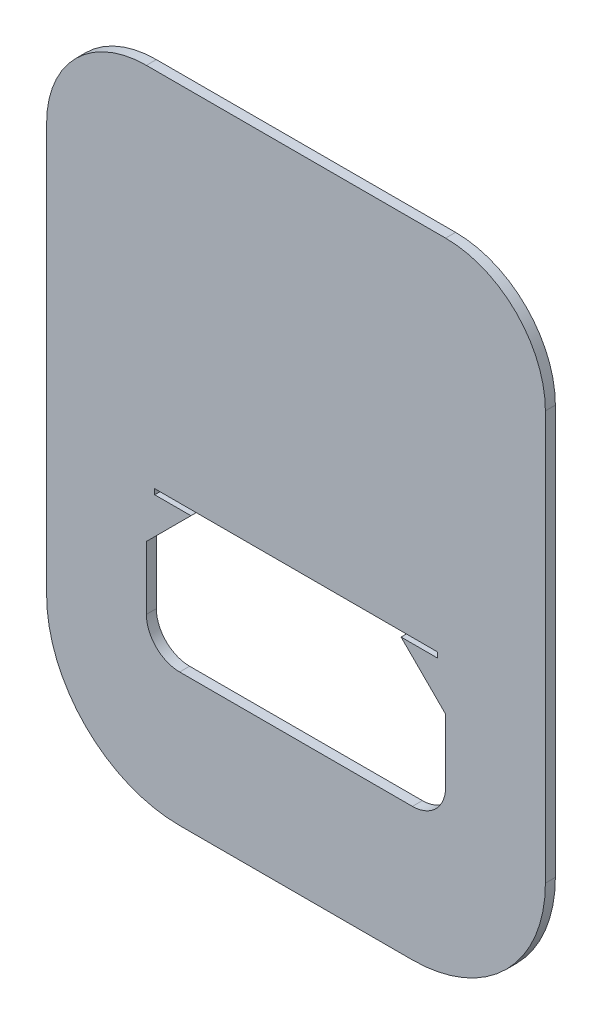
SolidWorks part; units mm, degrees
ref_plane "Front Plane" through (0, 0, 0) normal (0, 0, 1) x (1, 0, 0)
ref_plane "Top Plane" through (0, 0, 0) normal (0, 1, 0) x (1, 0, 0)
ref_plane "Right Plane" through (0, 0, 0) normal (1, 0, 0) x (0, 0, -1)
sketch "Sketch1" plane through (0, 0, 0) normal (0, 0, 1) x (1, 0, 0)
  line L0 (0, 96.5) -> (0, -96.5) construction
  line L1 (-75, 96.5) -> (75, 96.5) construction
  line L2 (-75, 96.5) -> (-75, -96.5) construction
  line L3 (-75, -96.5) -> (75, -96.5) construction
  line L4 (75, 96.5) -> (75, -96.5) construction
  line L5 (-45, 96.5) -> (45, 96.5)
  line L6 (-35, -96.5) -> (35, -96.5) construction
  line L7 (-75, 66.5) -> (75, 66.5) construction
  line L8 (-75, 66.5) -> (-75, -56.5)
  line L9 (-75, -56.5) -> (75, -56.5) construction
  line L10 (75, 66.5) -> (75, -56.5)
  line L11 (-0.5, -96.5) -> (0.5, -96.5) construction
  line L12 (-35, -96.5) -> (-0.5, -96.5)
  line L13 (0.5, -96.5) -> (35, -96.5)
  line L14 (-0.5, -96.5) -> (0.5, -96.5)
  arc A0 (-75, 66.5) -> (-45, 96.5) centre (-45, 66.5) cw
  arc A1 (45, 96.5) -> (75, 66.5) centre (45, 66.5) cw
  arc A2 (-75, -56.5) -> (-35, -96.5) centre (-35, -56.5) ccw
  arc A3 (35, -96.5) -> (75, -56.5) centre (35, -56.5) ccw
  point P10 (0, 96.5)
  point P19 (0, -96.5)
  point P23 (0, -96.5)
  dimension "D3" = 40
  dimension "D4" = 30
  dimension "D1" = 193
  dimension "D2" = 150
  dimension "D5" = 1
  dimension "D6" = 96.5
extrude "Boss-Extrude1" add sketch "Sketch1" along normal blind 3
sketch "Sketch2" plane through (0, 0, 3) normal (0, 0, 1) x (1, 0, 0)
  line L0 (0, -1.65) -> (0, 1.65) construction
  line L1 (-38, -56.5) -> (38, -56.5) construction
  line L2 (-45, -49.5) -> (-45, -19.5) construction
  line L3 (-38, -12.5) -> (38, -12.5) construction
  line L4 (45, -49.5) -> (45, -19.5) construction
  line L5 (-45, -56.5) -> (45, -12.5) construction
  line L6 (-45, -12.5) -> (45, -56.5) construction
  line L7 (-35, -96.5) -> (35, -96.5) construction
  line L9 (-45, -56.5) -> (45, -56.5)
  line L10 (-45, -56.5) -> (-45, -12.5)
  line L11 (-45, -12.5) -> (45, -12.5)
  line L12 (45, -56.5) -> (45, -12.5)
  line L13 (-45, -56.5) -> (45, -12.5) construction
  line L14 (-45, -12.5) -> (45, -56.5) construction
  arc A0 (38, -56.5) -> (45, -49.5) centre (38, -49.5) ccw construction
  arc A1 (38, -12.5) -> (45, -19.5) centre (38, -19.5) cw construction
  arc A2 (-45, -19.5) -> (-38, -12.5) centre (-38, -19.5) cw construction
  arc A3 (-38, -56.5) -> (-45, -49.5) centre (-38, -49.5) cw construction
  point P0 (0, -34.5)
  point P21 (0, -34.5)
  dimension "D4" = 7
  dimension "D1" = 84
  dimension "D2" = 40
  dimension "D3" = 90
extrude "Cut-Extrude1" cut sketch "Sketch2" against normal blind 10
fillet "Fillet1" radius 10 2 edges at (45, -56.5, 1.5) (-45, -56.5, 1.5)
chamfer "Chamfer1" distance 15 angle 45 2 edges at (45, -12.5, 1.5) (-45, -12.5, 1.5)
sketch "Sketch3" plane through (0, 0, 0) normal (0, 0, -1) x (-1, 0, 0)
  line L0 (0, 1.65) -> (0, -1.65) construction
  line L1 (-42.5, -14.1) -> (42.5, -14.1)
  line L2 (-42.5, -14.1) -> (-42.5, -12.5)
  line L3 (-42.5, -12.5) -> (42.5, -12.5)
  line L4 (42.5, -14.1) -> (42.5, -12.5)
  line L5 (-42.5, -14.1) -> (42.5, -12.5) construction
  line L6 (-42.5, -12.5) -> (42.5, -14.1) construction
  line L7 (30, -12.5) -> (-30, -12.5) construction
  point P0 (0, -13.3)
  dimension "D1" = 1.6
  dimension "D2" = 85
extrude "Cut-Extrude2" cut sketch "Sketch3" against normal blind 10
